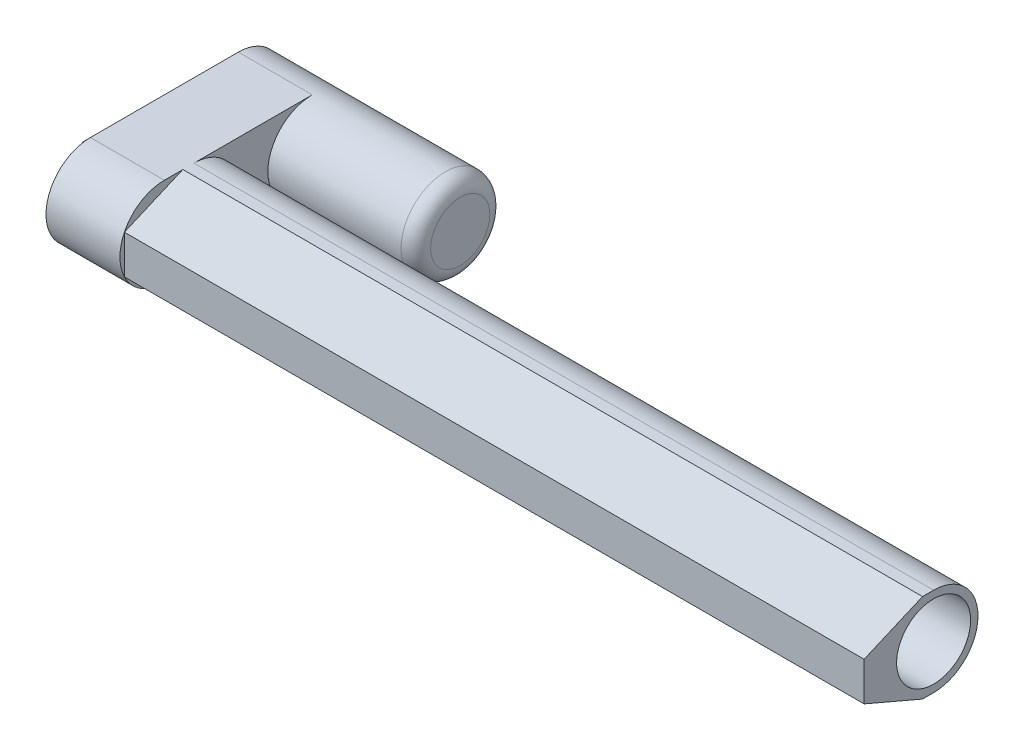
SolidWorks part; units mm, degrees
ref_plane "Front Plane" through (0, 0, 0) normal (0, 0, 1) x (1, 0, 0)
ref_plane "Top Plane" through (0, 0, 0) normal (0, 1, 0) x (1, 0, 0)
ref_plane "Right Plane" through (0, 0, 0) normal (1, 0, 0) x (0, 0, -1)
sketch "Sketch3" plane through (0, 0, 0) normal (1, 0, 0) x (0, 0, -1)
  line L0 (0, 0) -> (100, 0) construction
  line L1 (0, 30) -> (100, 30)
  line L2 (0, -30) -> (100, -30)
  arc A0 (0, 30) -> (0, -30) centre (0, 0) ccw
  arc A1 (100, -30) -> (100, 30) centre (100, 0) ccw
  point P3 (50, 0)
  dimension "D1" = 100
  dimension "80" = 30
extrude "Boss-Extrude3" add sketch "Sketch3" along normal blind 50 contours L1 A1 L2 A0
sketch "Sketch7" plane through (50, 0, 0) normal (1, 0, 0) x (0, 0, -1)
  circle A0 centre (100, 0) radius 30
  arc A1 (100, -30) -> (100, 30) centre (100, 0) ccw construction
  dimension "D1" = 60
extrude "Boss-Extrude4" add sketch "Sketch7" along normal blind 100
sketch "Sketch8" plane through (50, 0, 0) normal (1, 0, 0) x (0, 0, -1)
  line L0 (0, 0) -> (20, 0) construction
  line L1 (0, 30) -> (20, 30)
  line L2 (100, 30) -> (0, 30)
  line L3 (0, -30) -> (100, -30)
  line L6 (0, -30) -> (20, -30)
  arc A1 (0, 30) -> (0, -30) centre (0, 0) ccw
  arc A2 (20, -30) -> (20, 30) centre (20, 0) ccw
  arc A3 (100, 30) -> (100, -30) centre (100, 0) ccw
  arc A4 (0, 30) -> (0, -30) centre (0, 0) ccw
  arc A5 (100, 30) -> (100, -30) centre (100, 0) ccw
  point P2 (10, 0)
  dimension "D1" = 20
  dimension "D3" = 30
  dimension "D2" = 0
extrude "Boss-Extrude7" add sketch "Sketch8" along normal blind 500
sketch "Sketch9" plane through (550, 0, 0) normal (1, 0, 0) x (0, 0, -1)
  line L0 (0, 0) -> (20, 0) construction
  circle A1 centre (20, 0) radius 25
  dimension "D2" = 50
  dimension "D1" = 20
extrude "Cut-Extrude1" cut sketch "Sketch9" against normal blind 500
sketch "Sketch10" plane through (550, 0, 0) normal (1, 0, 0) x (0, 0, -1)
  line L0 (20, 30) -> (0, 30) construction
  line L1 (-27, 13.0767) -> (-27, -13.0767)
  line L2 (-27, -13.0767) -> (12.5298, -30)
  line L3 (12.5298, 30) -> (-27, 13.0767)
  line L4 (-30, 0) -> (0, 0) construction
  line L5 (0, -30) -> (20, -30) construction
  line L6 (0, -30) -> (12.5298, -30)
  line L7 (12.5298, 30) -> (0, 30)
  arc A0 (0, 30) -> (0, -30) centre (0, 0) ccw construction
  arc A2 (0, 30) -> (0, -30) centre (0, 0) ccw
  line M12 (0, -30) -> (20, -30)
  line M14 (20, 30) -> (0, 30)
  arc M15 (0, 30) -> (0, -30) centre (0, 0) ccw
  dimension "D1" = 27
  dimension "D2" = 43
extrude "Cut-Extrude2" cut sketch "Sketch10" against normal blind 500 contours L3 M14 M15 | L2 M15 M12 | L4 A2 L1 | L4 L1 M15
fillet "Fillet1" radius 10 1 edges at (150, 0, -130)
sketch "Sketch12" plane through (0, 0, 0) normal (-1, 0, 0) x (0, 0, 1)
  line L0 (0, 0) -> (0, -30) construction
  line L1 (0, -10) -> (-100, -10)
  line L2 (0, -10) -> (0, -30)
  line L3 (0, -30) -> (-100, -30)
  line L4 (-100, -10) -> (-100, -30)
  dimension "D1" = 20
extrude "Boss-Extrude8" add sketch "Sketch12" along normal blind 40
sketch "Sketch13" plane through (0, -30, 0) normal (0, -1, 0) x (1, 0, 0)
  line L0 (-40, -35) -> (-25, 0)
  line L1 (-40, -100) -> (-40, 0) construction
  line L2 (-40, 0) -> (0, 0) construction
  line L3 (-40, -50) -> (0, -50) construction
  line L4 (0, -100) -> (0, 0) construction
  line L5 (-40, -65) -> (-25, -100)
  line L6 (-40, -100) -> (0, -100) construction
  line L7 (-25, 0) -> (-40, 0)
  line L8 (-40, 0) -> (-40, -35)
  line L9 (-40, -65) -> (-40, -100)
  line L10 (-40, -100) -> (-25, -100)
  dimension "D1" = 35
  dimension "D2" = 15
extrude "Cut-Extrude3" cut sketch "Sketch13" against normal blind 40
sketch "Sketch14" plane through (0, -30, 0) normal (0, -1, 0) x (-1, 0, 0)
  line L0 (0, 100) -> (0, 0) construction
  line L1 (0, 50) -> (40, 50) construction
  line L2 (40, 65) -> (40, 35) construction
  circle A0 centre (20, 25) radius 10
  circle A1 centre (20, 75) radius 10
  dimension "D1" = 20
  dimension "D2" = 20
  dimension "D3" = 20
  dimension "D4" = 25
extrude "Cut-Extrude4" cut sketch "Sketch14" against normal blind 40
